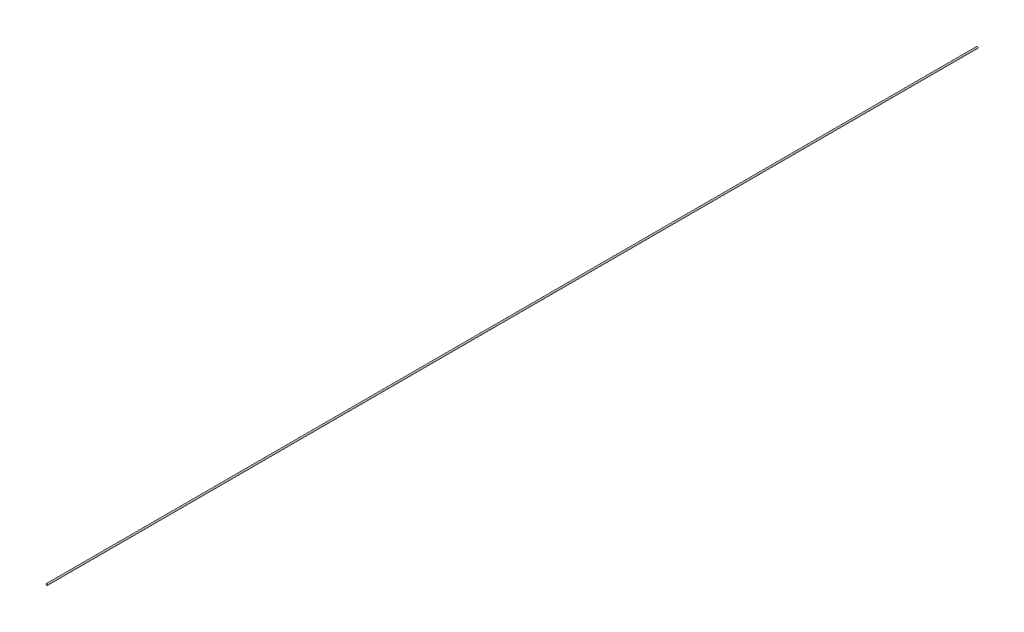
SolidWorks part; units mm, degrees
material "Hexcel AS4C (3000 丝)"
ref_plane "Front" through (0, 0, 0) normal (0, 0, 1) x (1, 0, 0)
ref_plane "Top" through (0, 0, 0) normal (0, 1, 0) x (1, 0, 0)
ref_plane "Right" through (0, 0, 0) normal (1, 0, 0) x (0, 0, -1)
other "Configuration Table"
sketch "草图1" plane through (0, 0, 0) normal (0, 0, 1) x (1, 0, 0)
  circle A0 centre (0, 0) radius 0.2
extrude "凸台-拉伸1" add sketch "草图1" along normal blind 233.5
